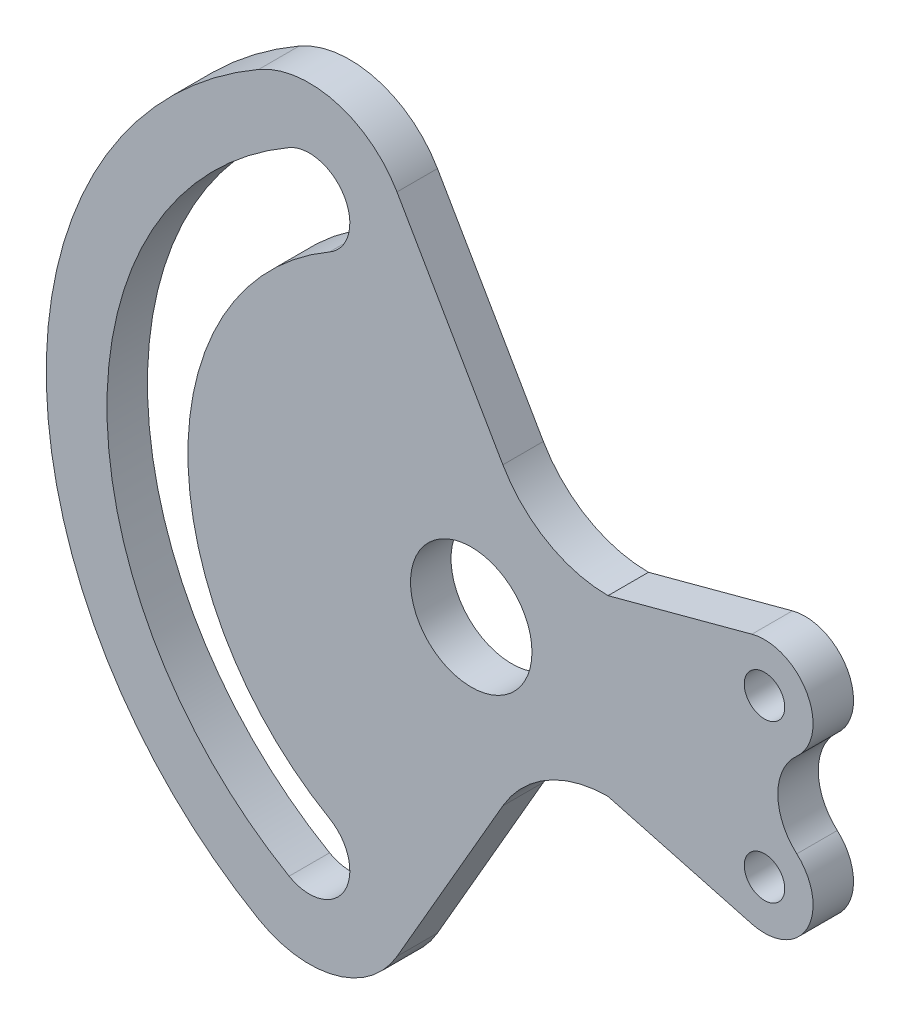
SolidWorks part; units mm, degrees
ref_plane "Front Plane" through (0, 0, 0) normal (0, 0, 1) x (1, 0, 0)
ref_plane "Top Plane" through (0, 0, 0) normal (0, 1, 0) x (1, 0, 0)
ref_plane "Right Plane" through (0, 0, 0) normal (1, 0, 0) x (0, 0, -1)
sketch "Sketch1" plane through (0, 0, 0) normal (0, 0, 1) x (1, 0, 0)
  line L0 (0, 0) -> (-123.5916, 0) construction
  line L1 (0, 0) -> (81.3452, 0) construction
  line L2 (0, 0) -> (72.4444, 19.4114) construction
  line L3 (69.3386, 31.0025) -> (33.7883, 21.4769)
  line L4 (7.8076, 36.4769) -> (-18.3494, 81.782)
  line L5 (0, 0) -> (-40, 69.282) construction
  line L6 (7.8076, -36.4769) -> (-18.3494, -81.782)
  line L7 (69.3386, -31.0025) -> (33.7883, -21.4769)
  circle A1 centre (0, 0) radius 15
  circle A2 centre (72.4444, 19.4114) radius 5
  arc A3 (80.4278, 10.4523) -> (69.3386, 31.0025) centre (72.4444, 19.4114) ccw
  arc A4 (80.4278, 10.4523) -> (80.4278, -10.4523) centre (89.7417, 0) ccw
  arc A5 (33.7883, 21.4769) -> (7.8076, 36.4769) centre (33.7883, 51.4769) cw
  arc A6 (-52.5, 90.9327) -> (-52.5, -90.9327) centre (0, 0) ccw
  arc A8 (-40, 69.282) -> (-40, -69.282) centre (0, 0) ccw construction
  arc A13 (-45, 77.9423) -> (-45, -77.9423) centre (0, 0) ccw
  arc A14 (-35, 60.6218) -> (-35, -60.6218) centre (0, 0) ccw
  arc A15 (-35, 60.6218) -> (-45, 77.9423) centre (-40, 69.282) ccw
  arc A16 (-45, -77.9423) -> (-35, -60.6218) centre (-40, -69.282) ccw
  arc A22 (-18.3494, 81.782) -> (-52.5, 90.9327) centre (-40, 69.282) ccw
  arc A23 (-18.3494, -81.782) -> (-52.5, -90.9327) centre (-40, -69.282) cw
  arc A24 (-27.5, 47.6314) -> (-52.5, 90.9327) centre (-40, 69.282) ccw construction
  arc A25 (-27.5, 47.6314) -> (-27.5, -47.6314) centre (0, 0) ccw construction
  arc A26 (-52.5, -90.9327) -> (-27.5, -47.6314) centre (-40, -69.282) ccw construction
  arc A27 (33.7883, -21.4769) -> (7.8076, -36.4769) centre (33.7883, -51.4769) ccw
  arc A28 (80.4278, -10.4523) -> (69.3386, -31.0025) centre (72.4444, -19.4114) cw
  circle A29 centre (72.4444, -19.4114) radius 5
  point P11 (-80, 0)
  point P23 (-50, 86.6025)
  point P24 (-45, 93.767)
  point P27 (-48.1947, 70.8006)
  point P28 (-36.8408, 27.1244)
  point P29 (-42.4567, 22.0727)
  point P30 (-48.323, 7.9971)
  point P31 (-50.1374, -7.2433)
  point P32 (-48.323, -17.7665)
  point P33 (-47.5973, -29.3782)
  point P34 (-123.5916, 0)
  point P35 (0, 0)
  point P36 (-18.8168, -47.356)
  point P37 (0, 0)
  point P38 (-104.8611, 0)
  point P39 (-50, 86.6025)
  point P43 (-30, -51.9615)
  point P44 (0, 0)
  point P45 (-30, 51.9615)
  point P47 (-15, 73.5748)
  point P48 (-50, 92.135)
  point P49 (-58.0278, 86.6025)
  point P50 (-50, 92.2259)
  point P51 (-49.9288, 86.6025)
  point P55 (-20.293, 72.6931)
  point P56 (-52.5, -90.9327)
  point P57 (0, 0)
  point P58 (26.9356, 47.6693)
  point P59 (33.4994, 51.9774)
  dimension "D1" = 24
  dimension "D2" = 10
  dimension "D5" = 14
  dimension "D6" = 15
  dimension "D7" = 30
  dimension "D9" = 25
  dimension "D10" = 10
  dimension "D11" = 80
  dimension "D3" = 75
  dimension "D4" = 15
  dimension "D8" = 60
extrude "Boss-Extrude1" add sketch "Sketch1" along normal blind 10
